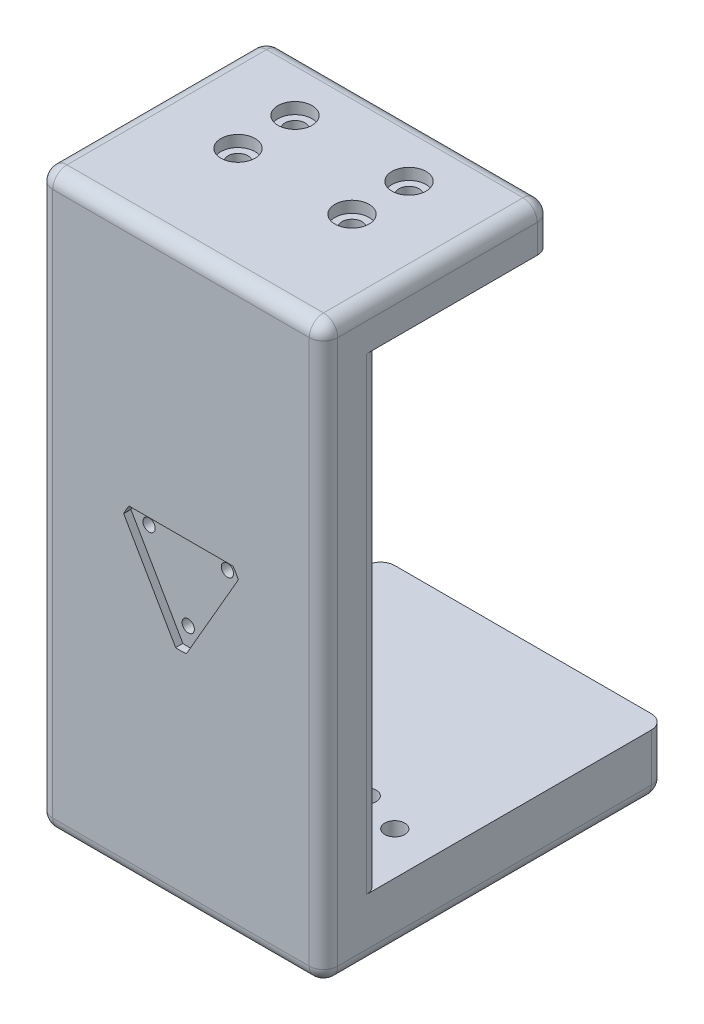
SolidWorks part; units mm, degrees
ref_plane "Front Plane" through (0, 0, 0) normal (0, 0, 1) x (1, 0, 0)
ref_plane "Top Plane" through (0, 0, 0) normal (0, 1, 0) x (1, 0, 0)
ref_plane "Right Plane" through (0, 0, 0) normal (1, 0, 0) x (0, 0, -1)
sketch "Sketch2" plane through (0, 0, 0) normal (0, 0, 1) x (1, 0, 0)
  line L1 (0, 0) -> (-50, 0)
  line L2 (0, 0) -> (0, -20)
  line L3 (0, -20) -> (-50, -20)
  line L4 (-50, 0) -> (-50, -20)
  dimension "D1" = 20
  dimension "D2" = 50
extrude "Boss-Extrude1" add sketch "Sketch2" against normal blind 100
sketch "Sketch3" plane through (0, 0, 0) normal (0, 1, 0) x (1, 0, 0)
  line L0 (-55, 0) -> (55, 0) construction
  line L1 (0, -55) -> (0, 55) construction
  line L2 (-50, 100) -> (-50, 0) construction
  circle A0 centre (-20, 25) radius 3.5
  circle A1 centre (-35, 20) radius 3.5
  dimension "D1" = 7
  dimension "D4" = 7
  dimension "D2" = 25
  dimension "D3" = 20
  dimension "D5" = 15
  dimension "D6" = 20
extrude "Cut-Extrude1" cut sketch "Sketch3" against normal through all
sketch "Sketch4" plane through (0, -20, 0) normal (0, -1, 0) x (1, 0, 0)
  line L0 (55, 0) -> (-55, 0) construction
  line L1 (-50, 0) -> (0, 0)
  line L2 (-50, 0) -> (-50, 20)
  line L3 (-50, 20) -> (0, 20)
  line L4 (0, 0) -> (0, 20)
  line L5 (-50, -100) -> (-50, 0) construction
  line L6 (0, -55) -> (0, 55) construction
  dimension "D1" = 20
extrude "Boss-Extrude2" add sketch "Sketch4" against normal blind 201
sketch "Sketch5" plane through (0, 0, 0) normal (0, 0, -1) x (-1, 0, 0)
  line L0 (0, 55) -> (0, -55) construction
  line L1 (50, 181) -> (0, 181)
  line L2 (50, 181) -> (50, 166)
  line L3 (50, 166) -> (0, 166)
  line L4 (0, 181) -> (0, 166)
  dimension "D1" = 15
extrude "Boss-Extrude3" add sketch "Sketch5" along normal blind 60
sketch "Sketch6" plane through (0, 166, 0) normal (0, -1, 0) x (1, 0, 0)
  line L0 (0, 0) -> (-50, 0) construction
  line L1 (-50, -60) -> (-50, 0) construction
  circle A0 centre (-20, -20) radius 3.5
  circle A1 centre (-20, -40) radius 3.5
  dimension "D1" = 7
  dimension "D3" = 30
  dimension "D4" = 7
  dimension "D2" = 20
  dimension "D5" = 20
extrude "Cut-Extrude2" cut sketch "Sketch6" against normal up to surface (15 mm away) up to face at (-25, 181, -20)
sketch "Sketch7" plane through (0, 181, 0) normal (0, 1, 0) x (1, 0, 0)
  circle A0 centre (-20, 40) radius 6
  circle A1 centre (-20, 20) radius 6
  dimension "D1" = 12
  dimension "D2" = 12
extrude "Cut-Extrude3" cut sketch "Sketch7" against normal blind 4
mirror "Mirror1" about plane through (0, 0, 0) normal (1, 0, 0) of "Cut-Extrude3", "Cut-Extrude2", "Boss-Extrude3", "Boss-Extrude2", "Cut-Extrude1", "Boss-Extrude1"
fillet "Fillet1" radius 5 7 edges at (-50, -20, -40) (0, -20, -100) (50, -20, -40) (-50, -10, -100) (50, -10, -100) (-50, 173.5, -60) (50, 173.5, -60)
fillet "Fillet2" radius 5 2 edges at (-50, 83, 0) (50, 83, 0)
fillet "Fillet3" radius 5 11 edges at (-50, 181, -17.5) (-48.5355, 181, -58.5355) (0, 181, -60) (48.5355, 181, -58.5355) (-48.5355, -18.5355, 20) (0, -20, 20) (48.5355, -18.5355, 20) (50, 181, -17.5) (-50, 83, 20) (0, 181, 20) (50, 83, 20)
sketch "Sketch15" plane through (0, 0, 20) normal (0, 0, 1) x (1, 0, 0)
  line L0 (0, 176) -> (0, -15) construction
  line L1 (45, 176) -> (-45, 176) construction
  line L2 (-45, -15) -> (45, -15) construction
  circle A0 centre (0, 80.5) radius 6.35
  dimension "D1" = 12.7
extrude "Boss-Extrude5" add sketch "Sketch15" along normal blind 7.9375
sketch "Sketch8" plane through (0, 0, 20) normal (0, 0, 1) x (1, 0, 0)
  line L0 (0, -55) -> (0, 55) construction
  line L1 (-45, 80.5) -> (45, 80.5) construction
  line L2 (-45, 176) -> (-45, -15) construction
  line L3 (45, -15) -> (45, 176) construction
  circle A0 centre (0, 80.5) radius 50.8
  dimension "D1" = 101.6
extrude "Boss-Extrude4" [suppressed] add sketch "Sketch8" against normal up to surface (20 mm away)
sketch "Sketch9" [suppressed] plane through (0, 0, 20) normal (0, 0, 1) x (1, 0, 0)
  line L0 (-50.8, 80.5) -> (50.8, 80.5) construction
  line L1 (0, 55.1) -> (0, 105.9) construction
  line L2 (-25.4, 80.5) -> (25.4, 80.5) construction
  line L3 (5.08, 55.1) -> (5.08, 75.42)
  line L4 (-25.4, 75.42) -> (-5.08, 75.42)
  line L5 (-5.08, 55.1) -> (-5.08, 75.42)
  line L6 (-25.4, 85.58) -> (-5.08, 85.58)
  line L7 (5.08, 85.58) -> (25.4, 85.58)
  line L8 (-5.08, 85.58) -> (-5.08, 105.9)
  line L9 (5.08, 85.58) -> (5.08, 105.9)
  line L10 (5.08, 75.42) -> (25.4, 75.42)
  arc A0 (-45, 104.072) -> (-45, 56.928) centre (0, 80.5) ccw construction
  arc A1 (45, 56.928) -> (45, 104.072) centre (0, 80.5) ccw construction
  arc A2 (5.08, 55.1) -> (-5.08, 55.1) centre (0, 55.1) cw
  arc A3 (5.08, 105.9) -> (-5.08, 105.9) centre (0, 105.9) ccw
  arc A4 (-25.4, 75.42) -> (-25.4, 85.58) centre (-25.4, 80.5) cw
  arc A5 (25.4, 75.42) -> (25.4, 85.58) centre (25.4, 80.5) ccw
  point P10 (0, 80.5)
  point P13 (0, 80.5)
  point P26 (0, 80.5)
  dimension "D5" = 5.08
  dimension "D6" = 5.08
  dimension "D1" = 50.8
  dimension "D2" = 50.8
  dimension "D3" = 10.16
  dimension "D4" = 10.16
extrude "Cut-Extrude4" [suppressed] cut sketch "Sketch9" against normal blind 5.5
sketch "Sketch10" [suppressed] plane through (0, 0, 14.5) normal (0, 0, 1) x (1, 0, 0)
  line L24 (6.58, 55.1) -> (6.58, 73.92)
  line L25 (6.58, 73.92) -> (25.4, 73.92)
  line L26 (25.4, 87.08) -> (6.58, 87.08)
  line L27 (6.58, 87.08) -> (6.58, 105.9)
  line L28 (-6.58, 105.9) -> (-6.58, 87.08)
  line L29 (-6.58, 87.08) -> (-25.4, 87.08)
  line L30 (-25.4, 73.92) -> (-6.58, 73.92)
  line L31 (-6.58, 73.92) -> (-6.58, 55.1)
  line L32 (6.58, 55.1) -> (6.58, 73.92)
  line L33 (6.58, 73.92) -> (25.4, 73.92)
  line L34 (25.4, 87.08) -> (6.58, 87.08)
  line L35 (6.58, 87.08) -> (6.58, 105.9)
  line L36 (-6.58, 105.9) -> (-6.58, 87.08)
  line L37 (-6.58, 87.08) -> (-25.4, 87.08)
  line L38 (-25.4, 73.92) -> (-6.58, 73.92)
  line L39 (-6.58, 73.92) -> (-6.58, 55.1)
  arc A12 (-6.58, 55.1) -> (6.58, 55.1) centre (0, 55.1) ccw
  arc A13 (25.4, 73.92) -> (25.4, 87.08) centre (25.4, 80.5) ccw
  arc A14 (6.58, 105.9) -> (-6.58, 105.9) centre (0, 105.9) ccw
  arc A15 (-25.4, 87.08) -> (-25.4, 73.92) centre (-25.4, 80.5) ccw
  arc A16 (-6.58, 55.1) -> (6.58, 55.1) centre (0, 55.1) ccw
  arc A17 (25.4, 73.92) -> (25.4, 87.08) centre (25.4, 80.5) ccw
  arc A18 (6.58, 105.9) -> (-6.58, 105.9) centre (0, 105.9) ccw
  arc A19 (-25.4, 87.08) -> (-25.4, 73.92) centre (-25.4, 80.5) ccw
  dimension "D1" = 1.5
extrude "Cut-Extrude5" [suppressed] cut sketch "Sketch10" along normal up to surface (5.5 mm away)
sketch "Sketch11" plane through (0, 0, 20) normal (0, 0, 1) x (1, 0, 0)
  circle A0 centre (0, 121.394) radius 2.25
  circle A1 centre (0, 39.606) radius 2.25 construction
  circle A2 centre (-40.894, 80.5) radius 2.25 construction
  circle A3 centre (40.894, 80.5) radius 2.25 construction
  circle A4 centre (0, 39.606) radius 2.25
  circle A5 centre (-40.894, 80.5) radius 2.25
  circle A6 centre (40.894, 80.5) radius 2.25
extrude "Cut-Extrude6" [suppressed] cut sketch "Sketch11" against normal through all
sketch "Sketch12" [suppressed] plane through (0, 0, 0) normal (0, 0, -1) x (-1, 0, 0)
  circle A0 centre (0, 121.394) radius 6
  circle A1 centre (-40.894, 80.5) radius 6
  circle A2 centre (40.894, 80.5) radius 6
  circle A3 centre (0, 39.606) radius 6
  dimension "D1" = 12
extrude "Cut-Extrude7" [suppressed] cut sketch "Sketch12" against normal blind 5
sketch "Sketch14" plane through (0, -20, 0) normal (0, -1, 0) x (1, 0, 0)
  circle A0 centre (-35, -20) radius 6.5
  circle A1 centre (-20, -25) radius 6.5
  circle A2 centre (20, -25) radius 6.5
  circle A3 centre (35, -20) radius 6.5
  dimension "D1" = 13
extrude "Cut-Extrude8" [suppressed] cut sketch "Sketch14" against normal blind 5
other "Move Face1" face at (23.5, 0, -25) parameters "D1"=1.74
sketch "Sketch16" plane through (0, 0, 20) normal (0, 0, 1) x (1, 0, 0)
  line L0 (-20.118, 89.9454) -> (-1.879, 58.3546)
  line L1 (1.879, 58.3546) -> (20.118, 89.9454)
  line L2 (18.239, 93.2) -> (-18.239, 93.2)
  arc A0 (-1.879, 58.3546) -> (1.879, 58.3546) centre (0, 80.5) ccw
  arc A1 (20.118, 89.9454) -> (18.239, 93.2) centre (0, 80.5) ccw
  arc A2 (-18.239, 93.2) -> (-20.118, 89.9454) centre (0, 80.5) ccw
  circle A3 centre (0, 80.5) radius 25
  point P15 (0, 80.5)
  dimension "D1" = 22.225
  dimension "D2" = 22.225
  dimension "D3" = 22.225
  dimension "D7" = 50
  dimension "D4" = 31.5909
  dimension "D5" = 34.8454
  dimension "D6" = 1.879
sketch "Sketch17" plane through (0, 0, 27.9375) normal (0, 0, 1) x (1, 0, 0)
  circle A1 centre (0, 80.5) radius 6.35
  circle A2 centre (0, 80.5) radius 6.35
  dimension "D1" = 0
extrude "Cut-Extrude9" cut sketch "Sketch17" against normal up to surface (7.9375 mm away) up to face at (6.35, 80.5, 20)
extrude "Boss-Extrude7" add sketch "Sketch16" along normal blind 2.54
sketch "Sketch18" plane through (0, 0, 20) normal (0, 0, 1) x (1, 0, 0)
  line L2 (0, 64.6275) -> (0, 88.44) construction
  line L3 (0, 88.44) -> (-13.7482, 88.44) construction
  line L4 (0, 88.44) -> (13.7482, 88.44) construction
  circle A0 centre (0, 64.6275) radius 2.15
  circle A1 centre (-13.7482, 88.44) radius 2.15
  circle A2 centre (13.7482, 88.44) radius 2.15
  circle A3 centre (0, 80.5) radius 25 construction
  dimension "D5" = 4.3
  dimension "D1" = 13.7482
  dimension "D2" = 13.7482
  dimension "D3" = 23.8125
  dimension "D4" = 7.94
extrude "Cut-Extrude10" cut sketch "Sketch18" against normal through all
sketch "Sketch19" plane through (0, 0, 20) normal (0, 0, 1) x (1, 0, 0)
  line L3 (-20.118, 89.9454) -> (-1.879, 58.3546)
  line L4 (1.879, 58.3546) -> (20.118, 89.9454)
  line L5 (18.239, 93.2) -> (-18.239, 93.2)
  line L6 (-20.118, 89.9454) -> (-1.879, 58.3546)
  line L7 (1.879, 58.3546) -> (20.118, 89.9454)
  line L8 (18.239, 93.2) -> (-18.239, 93.2)
  arc A3 (-18.239, 93.2) -> (-20.118, 89.9454) centre (0, 80.5) ccw
  arc A4 (-1.879, 58.3546) -> (1.879, 58.3546) centre (0, 80.5) ccw
  arc A5 (20.118, 89.9454) -> (18.239, 93.2) centre (0, 80.5) ccw
  arc A6 (-18.239, 93.2) -> (-20.118, 89.9454) centre (0, 80.5) ccw
  arc A7 (-1.879, 58.3546) -> (1.879, 58.3546) centre (0, 80.5) ccw
  arc A8 (20.118, 89.9454) -> (18.239, 93.2) centre (0, 80.5) ccw
  dimension "D1" = 0
extrude "Cut-Extrude11" cut sketch "Sketch19" against normal blind 2.54
sketch "Sketch20" plane through (0, 0, 22.54) normal (0, 0, 1) x (1, 0, 0)
  circle A1 centre (0, 80.5) radius 25
  circle A2 centre (0, 80.5) radius 25
  dimension "D1" = 0
extrude "Cut-Extrude12" cut sketch "Sketch20" against normal up to surface (2.54 mm away) up to face at (0, 80.5, 20)
sketch "Sketch21" plane through (0, 0, 0) normal (0, 0, -1) x (-1, 0, 0)
  circle A0 centre (-13.7482, 88.44) radius 5
  circle A1 centre (13.7482, 88.44) radius 5
  circle A2 centre (0, 64.6275) radius 5
  dimension "D1" = 10
  dimension "D2" = 10
  dimension "D3" = 10
extrude "Cut-Extrude13" cut sketch "Sketch21" against normal blind 2
